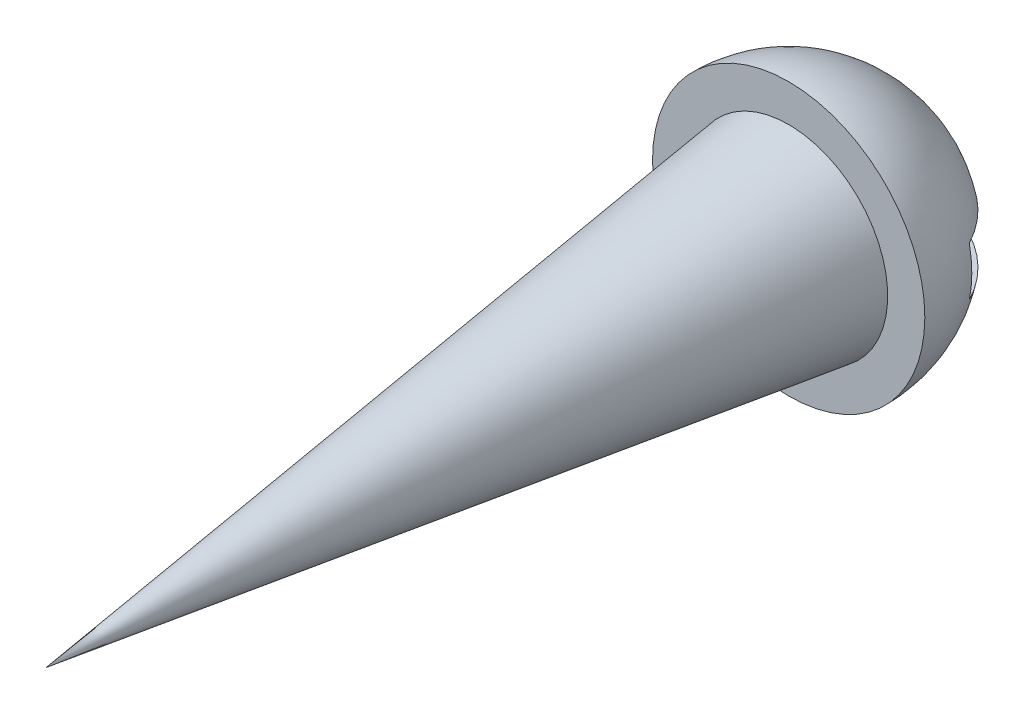
SolidWorks part; units mm, degrees
material "Stainless Steel (ferritic)"
ref_plane "Front Plane" through (0, 0, 0) normal (0, 0, 1) x (1, 0, 0)
ref_plane "Top Plane" through (0, 0, 0) normal (0, 1, 0) x (1, 0, 0)
ref_plane "Right Plane" through (0, 0, 0) normal (1, 0, 0) x (0, 0, -1)
sketch "Sketch2" plane through (0, 0, 0) normal (0, 1, 0) x (1, 0, 0)
  line L0 (0, 0) -> (2, 0)
  line L1 (2, 0) -> (0, -15)
  line L2 (0, -15) -> (0, 0)
  dimension "D1" = 2
  dimension "D2" = 15
revolve "Revolve1" add sketch "Sketch2" angle 360 about L2
sketch "Sketch12" plane through (0, 0, 0) normal (0, 0, 1) x (1, 0, 0)
  line L0 (0, 2.75) -> (0, -2.75)
  arc A0 (0, 2.75) -> (0, -2.75) centre (0, 0) ccw
  point P5 (0, 0)
  dimension "D1" = 5.5
revolve "Revolve2" add sketch "Sketch12" angle 180 about L0
sketch "Sketch13" plane through (0, 0, 0) normal (1, 0, 0) x (0, 0, -1)
  line L1 (1.25, 0.5) -> (4.25, 0.5)
  line L2 (1.25, 0.5) -> (1.25, -0.5)
  line L3 (1.25, -0.5) -> (4.25, -0.5)
  line L4 (4.25, 0.5) -> (4.25, -0.5)
  line L5 (1.25, 0.5) -> (4.25, -0.5) construction
  line L6 (1.25, -0.5) -> (4.25, 0.5) construction
  arc A0 (0, -2.75) -> (0, 2.75) centre (0, 0) ccw construction
  point P0 (2.75, 0)
  dimension "D1" = 1
  dimension "D2" = 3
extrude "Cut-Extrude1" cut sketch "Sketch13" against normal mid plane 10
sketch "Sketch14" plane through (0, 0, 0) normal (0, 1, 0) x (1, 0, 0)
  line L0 (-3.025, 0) -> (3.025, 0) construction
  point P0 (0, -15)
ref_plane "Plane2" through (0, 0, 15) normal (0, 0, 1) x (1, 0, 0)
